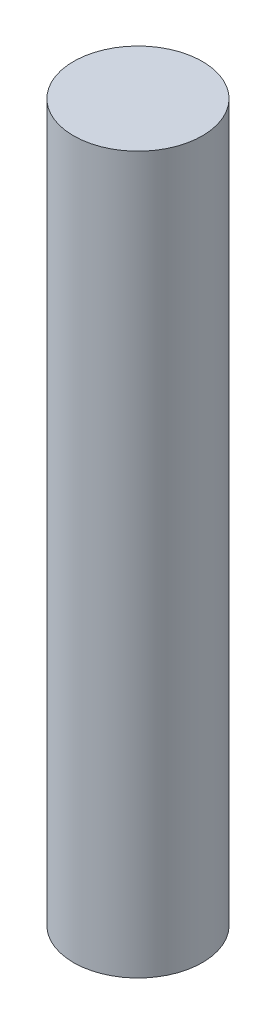
SolidWorks part; units mm, degrees
ref_plane "Front Plane" through (0, 0, 0) normal (0, 0, 1) x (1, 0, 0)
ref_plane "Top Plane" through (0, 0, 0) normal (0, 1, 0) x (1, 0, 0)
ref_plane "Right Plane" through (0, 0, 0) normal (1, 0, 0) x (0, 0, -1)
sketch "Sketch1" plane through (0, 0, 0) normal (0, 1, 0) x (1, 0, 0)
  circle A0 centre (0, 0) radius 4.5
  dimension "D1" = 9
extrude "Boss-Extrude1" add sketch "Sketch1" along normal blind 50
